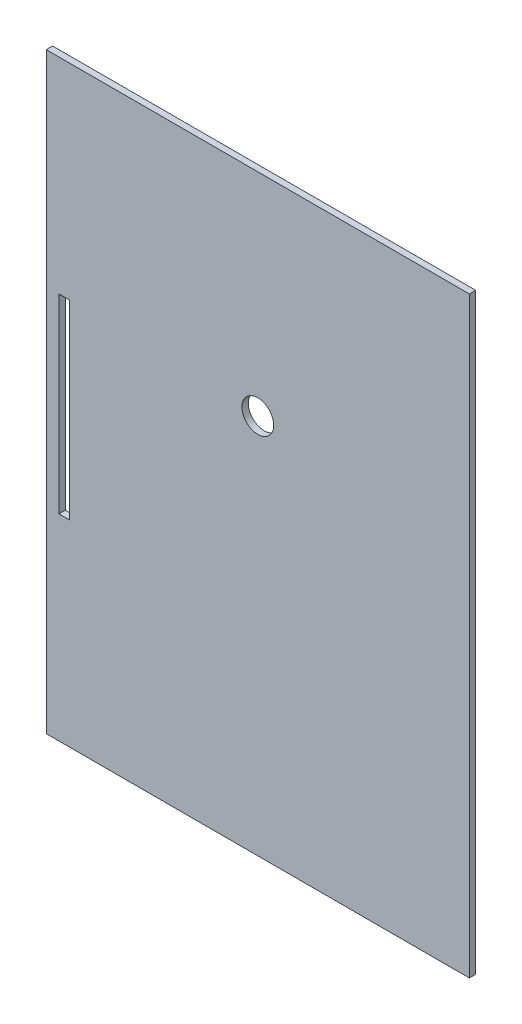
SolidWorks part; units mm, degrees
ref_plane "前基準面" through (0, 0, 0) normal (0, 0, 1) x (1, 0, 0)
ref_plane "上基準面" through (0, 0, 0) normal (0, 1, 0) x (1, 0, 0)
ref_plane "右基準面" through (0, 0, 0) normal (1, 0, 0) x (0, 0, -1)
sketch "草圖1" plane through (0, 0, 0) normal (0, 0, 1) x (1, 0, 0)
  line L1 (-100, 140) -> (100, 140)
  line L2 (-100, 140) -> (-100, -140)
  line L3 (-100, -140) -> (100, -140)
  line L4 (100, 140) -> (100, -140)
  line L7 (-94, 43) -> (-89, 43)
  line L8 (-94, 43) -> (-94, -47)
  line L9 (-94, -47) -> (-89, -47)
  line L10 (-89, 43) -> (-89, -47)
  circle A0 centre (0, 40) radius 7.5
  point P0 (0, 0)
  dimension "D8" = 15
  dimension "D1" = 200
  dimension "D2" = 280
  dimension "D3" = 5
  dimension "D4" = 90
  dimension "D5" = 97
  dimension "D6" = 6
  dimension "D7" = 100
extrude "填料-伸長1" add sketch "草圖1" along normal blind 3
